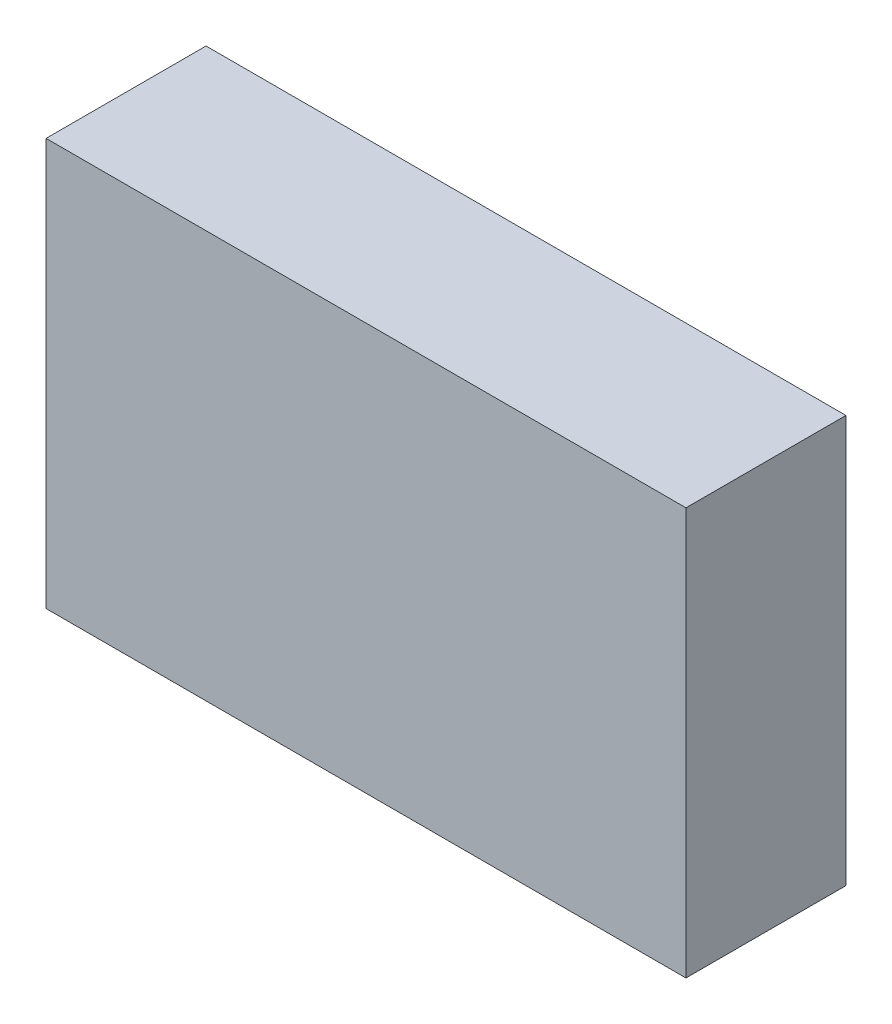
SolidWorks part; units mm, degrees
ref_plane "前视基准面" through (0, 0, 0) normal (0, 0, 1) x (1, 0, 0)
ref_plane "上视基准面" through (0, 0, 0) normal (0, 1, 0) x (1, 0, 0)
ref_plane "右视基准面" through (0, 0, 0) normal (1, 0, 0) x (0, 0, -1)
sketch "草图1" plane through (0, 0, 0) normal (0, 0, 1) x (1, 0, 0)
  line L0 (-1.1, -0.7) -> (-1.1, -0.575)
  line L1 (-1.1, -0.575) -> (-1.1, 0.575)
  line L2 (-1.1, 0.575) -> (-1.1, 0.7)
  line L3 (-1.1, 0.7) -> (1.1, 0.7)
  line L4 (1.1, 0.7) -> (1.1, -0.7)
  line L5 (1.1, -0.7) -> (-1.1, -0.7)
extrude "Component_Outline" add sketch "草图1" along normal blind 0.55 separate body
sketch3d "3D草图1"
  line L0 (0, 0, 0) -> (1, 0, 0)
  line L1 (0, 0, 0) -> (0, 1, 0)
  line L2 (0, 0, 0) -> (0, 0, 1)
  point P0 (0, 0, 0)
